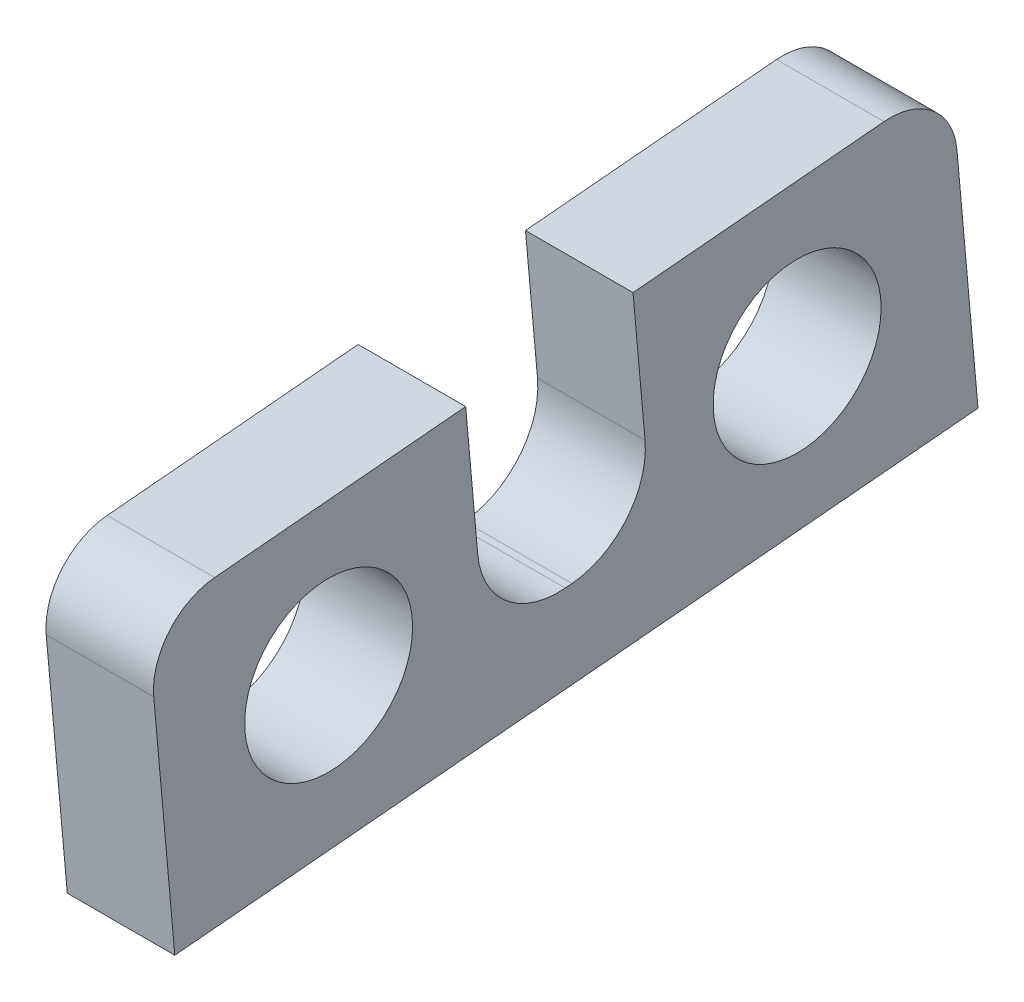
SolidWorks part; units mm, degrees
ref_plane "Спереди" through (0, 0, 0) normal (0, 0, 1) x (1, 0, 0)
ref_plane "Сверху" through (0, 0, 0) normal (0, 1, 0) x (1, 0, 0)
ref_plane "Справа" through (0, 0, 0) normal (1, 0, 0) x (0, 0, -1)
sketch "Эскиз1" plane through (0, 0, 0) normal (1, 0, 0) x (0, 0, -1)
  line L0 (2.7142, 32.8545) -> (3.0273, 29.3685) construction
  line L1 (-2.1063, 33.4255) -> (1.6287, 33.761) construction
  line L2 (-1.9273, 31.4335) -> (-2.1063, 33.4255) construction
  line L3 (-3.1148, 30.122) -> (-3.0152, 30.131) construction
  line L4 (-4.5962, 33.2019) -> (-4.4173, 31.2099) construction
  line L5 (-8.3312, 32.8664) -> (-4.5962, 33.2019) construction
  line L6 (-8.9246, 28.295) -> (-9.2377, 31.7809) construction
  line L8 (2.7142, 32.8545) -> (3.0273, 29.3685)
  line L9 (-2.1063, 33.4255) -> (1.6287, 33.761)
  line L10 (-1.9273, 31.4335) -> (-2.1063, 33.4255)
  line L11 (-3.1148, 30.122) -> (-3.0152, 30.131)
  line L12 (-4.5962, 33.2019) -> (-4.4173, 31.2099)
  line L13 (-8.3312, 32.8664) -> (-4.5962, 33.2019)
  line L14 (-8.9246, 28.295) -> (-9.2377, 31.7809)
  line L15 (-8.9246, 28.295) -> (3.0273, 29.3685) construction
  line L16 (-8.9246, 28.295) -> (3.0273, 29.3685)
  arc A0 (2.7142, 32.8545) -> (1.6287, 33.761) centre (1.7182, 32.765) ccw construction
  arc A1 (-3.0152, 30.131) -> (-1.9273, 31.4335) centre (-3.1225, 31.3262) ccw construction
  arc A2 (-4.4173, 31.2099) -> (-3.1148, 30.122) centre (-3.2221, 31.3172) ccw construction
  arc A3 (-8.3312, 32.8664) -> (-9.2377, 31.7809) centre (-8.2417, 31.8704) ccw construction
  arc A4 (2.7142, 32.8545) -> (1.6287, 33.761) centre (1.7182, 32.765) ccw
  arc A5 (-3.0152, 30.131) -> (-1.9273, 31.4335) centre (-3.1225, 31.3262) ccw
  arc A6 (-4.4173, 31.2099) -> (-3.1148, 30.122) centre (-3.2221, 31.3172) ccw
  arc A7 (-8.3312, 32.8664) -> (-9.2377, 31.7809) centre (-8.2417, 31.8704) ccw
  circle A8 centre (-6.6359, 30.7596) radius 1.25 construction
  circle A9 centre (0.336, 31.3858) radius 1.25 construction
  circle A10 centre (-6.6359, 30.7596) radius 1.25
  circle A11 centre (0.336, 31.3858) radius 1.25
extrude "Бобышка-Вытянуть1" add sketch "Эскиз1" along normal blind 1.6
